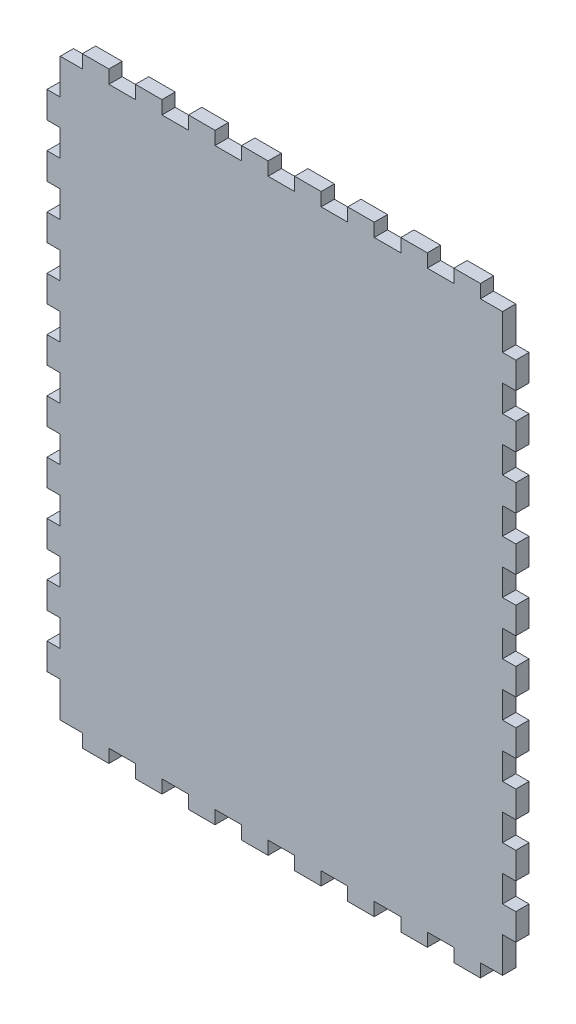
SolidWorks part; units mm, degrees
ref_plane "Front Plane" through (0, 0, 0) normal (0, 0, 1) x (1, 0, 0)
ref_plane "Top Plane" through (0, 0, 0) normal (0, 1, 0) x (1, 0, 0)
ref_plane "Right Plane" through (0, 0, 0) normal (1, 0, 0) x (0, 0, -1)
sketch "Model" plane through (0, 0, 0) normal (0, 0, 1) x (1, 0, 0)
  line L0 (496, 269) -> (496, 253)
  line L1 (496, 253) -> (490, 253)
  line L2 (490, 253) -> (490, 241)
  line L3 (490, 241) -> (496, 241)
  line L4 (496, 241) -> (496, 229)
  line L5 (496, 229) -> (490, 229)
  line L6 (490, 229) -> (490, 217)
  line L7 (490, 217) -> (496, 217)
  line L8 (496, 217) -> (496, 205)
  line L9 (496, 205) -> (490, 205)
  line L10 (490, 205) -> (490, 193)
  line L11 (490, 193) -> (496, 193)
  line L12 (496, 193) -> (496, 181)
  line L13 (496, 181) -> (490, 181)
  line L14 (490, 181) -> (490, 169)
  line L15 (490, 169) -> (496, 169)
  line L16 (496, 169) -> (496, 157)
  line L17 (496, 157) -> (490, 157)
  line L18 (490, 157) -> (490, 145)
  line L19 (490, 145) -> (496, 145)
  line L20 (496, 145) -> (496, 133)
  line L21 (496, 133) -> (490, 133)
  line L22 (490, 133) -> (490, 121)
  line L23 (490, 121) -> (496, 121)
  line L24 (496, 121) -> (496, 109)
  line L25 (496, 109) -> (490, 109)
  line L26 (490, 109) -> (490, 97)
  line L27 (490, 97) -> (496, 97)
  line L28 (496, 97) -> (496, 85)
  line L29 (496, 85) -> (490, 85)
  line L30 (490, 85) -> (490, 73)
  line L31 (490, 73) -> (496, 73)
  line L32 (496, 73) -> (496, 61)
  line L33 (496, 61) -> (490, 61)
  line L34 (490, 61) -> (490, 49)
  line L35 (490, 49) -> (496, 49)
  line L36 (496, 49) -> (496, 37)
  line L37 (496, 37) -> (490, 37)
  line L38 (490, 37) -> (490, 25)
  line L39 (490, 25) -> (496, 25)
  line L40 (496, 25) -> (496, 13)
  line L41 (496, 13) -> (496, 9)
  line L42 (496, 9) -> (506, 9)
  line L43 (506, 9) -> (506, 3)
  line L44 (506, 3) -> (518, 3)
  line L45 (518, 3) -> (518, 9)
  line L46 (518, 9) -> (530, 9)
  line L47 (530, 9) -> (530, 3)
  line L48 (530, 3) -> (542, 3)
  line L49 (542, 3) -> (542, 9)
  line L50 (542, 9) -> (554, 9)
  line L51 (554, 9) -> (554, 3)
  line L52 (554, 3) -> (566, 3)
  line L53 (566, 3) -> (566, 9)
  line L54 (566, 9) -> (578, 9)
  line L55 (578, 9) -> (578, 3)
  line L56 (578, 3) -> (590, 3)
  line L57 (590, 3) -> (590, 9)
  line L58 (590, 9) -> (602, 9)
  line L59 (602, 9) -> (602, 3)
  line L60 (602, 3) -> (614, 3)
  line L61 (614, 3) -> (614, 9)
  line L62 (614, 9) -> (626, 9)
  line L63 (626, 9) -> (626, 3)
  line L64 (626, 3) -> (638, 3)
  line L65 (638, 3) -> (638, 9)
  line L66 (638, 9) -> (650, 9)
  line L67 (650, 9) -> (650, 3)
  line L68 (650, 3) -> (662, 3)
  line L69 (662, 3) -> (662, 9)
  line L70 (662, 9) -> (674, 9)
  line L71 (674, 9) -> (674, 3)
  line L72 (674, 3) -> (686, 3)
  line L73 (686, 3) -> (686, 9)
  line L74 (686, 9) -> (696, 9)
  line L75 (696, 9) -> (696, 25)
  line L76 (696, 25) -> (702, 25)
  line L77 (702, 25) -> (702, 37)
  line L78 (702, 37) -> (696, 37)
  line L79 (696, 37) -> (696, 49)
  line L80 (696, 49) -> (702, 49)
  line L81 (702, 49) -> (702, 61)
  line L82 (702, 61) -> (696, 61)
  line L83 (696, 61) -> (696, 73)
  line L84 (696, 73) -> (702, 73)
  line L85 (702, 73) -> (702, 85)
  line L86 (702, 85) -> (696, 85)
  line L87 (696, 85) -> (696, 97)
  line L88 (696, 97) -> (702, 97)
  line L89 (702, 97) -> (702, 109)
  line L90 (702, 109) -> (696, 109)
  line L91 (696, 109) -> (696, 121)
  line L92 (696, 121) -> (702, 121)
  line L93 (702, 121) -> (702, 133)
  line L94 (702, 133) -> (696, 133)
  line L95 (696, 133) -> (696, 145)
  line L96 (696, 145) -> (702, 145)
  line L97 (702, 145) -> (702, 157)
  line L98 (702, 157) -> (696, 157)
  line L99 (696, 157) -> (696, 169)
  line L100 (696, 169) -> (702, 169)
  line L101 (702, 169) -> (702, 181)
  line L102 (702, 181) -> (696, 181)
  line L103 (696, 181) -> (696, 193)
  line L104 (696, 193) -> (702, 193)
  line L105 (702, 193) -> (702, 205)
  line L106 (702, 205) -> (696, 205)
  line L107 (696, 205) -> (696, 217)
  line L108 (696, 217) -> (702, 217)
  line L109 (702, 217) -> (702, 229)
  line L110 (702, 229) -> (696, 229)
  line L111 (696, 229) -> (696, 241)
  line L112 (696, 241) -> (702, 241)
  line L113 (702, 241) -> (702, 253)
  line L114 (702, 253) -> (696, 253)
  line L115 (696, 253) -> (696, 265)
  line L116 (696, 265) -> (696, 269)
  line L117 (696, 269) -> (686, 269)
  line L118 (686, 269) -> (686, 275)
  line L119 (686, 275) -> (674, 275)
  line L120 (674, 275) -> (674, 269)
  line L121 (674, 269) -> (662, 269)
  line L122 (662, 269) -> (662, 275)
  line L123 (662, 275) -> (650, 275)
  line L124 (650, 275) -> (650, 269)
  line L125 (650, 269) -> (638, 269)
  line L126 (638, 269) -> (638, 275)
  line L127 (638, 275) -> (626, 275)
  line L128 (626, 275) -> (626, 269)
  line L129 (626, 269) -> (614, 269)
  line L130 (614, 269) -> (614, 275)
  line L131 (614, 275) -> (602, 275)
  line L132 (602, 275) -> (602, 269)
  line L133 (602, 269) -> (590, 269)
  line L134 (590, 269) -> (590, 275)
  line L135 (590, 275) -> (578, 275)
  line L136 (578, 275) -> (578, 269)
  line L137 (578, 269) -> (566, 269)
  line L138 (566, 269) -> (566, 275)
  line L139 (566, 275) -> (554, 275)
  line L140 (554, 275) -> (554, 269)
  line L141 (554, 269) -> (542, 269)
  line L142 (542, 269) -> (542, 275)
  line L143 (542, 275) -> (530, 275)
  line L144 (530, 275) -> (530, 269)
  line L145 (530, 269) -> (518, 269)
  line L146 (518, 269) -> (518, 275)
  line L147 (518, 275) -> (506, 275)
  line L148 (506, 275) -> (506, 269)
  line L149 (506, 269) -> (496, 269)
extrude "Boss-Extrude1" add sketch "Model" along normal blind 6
